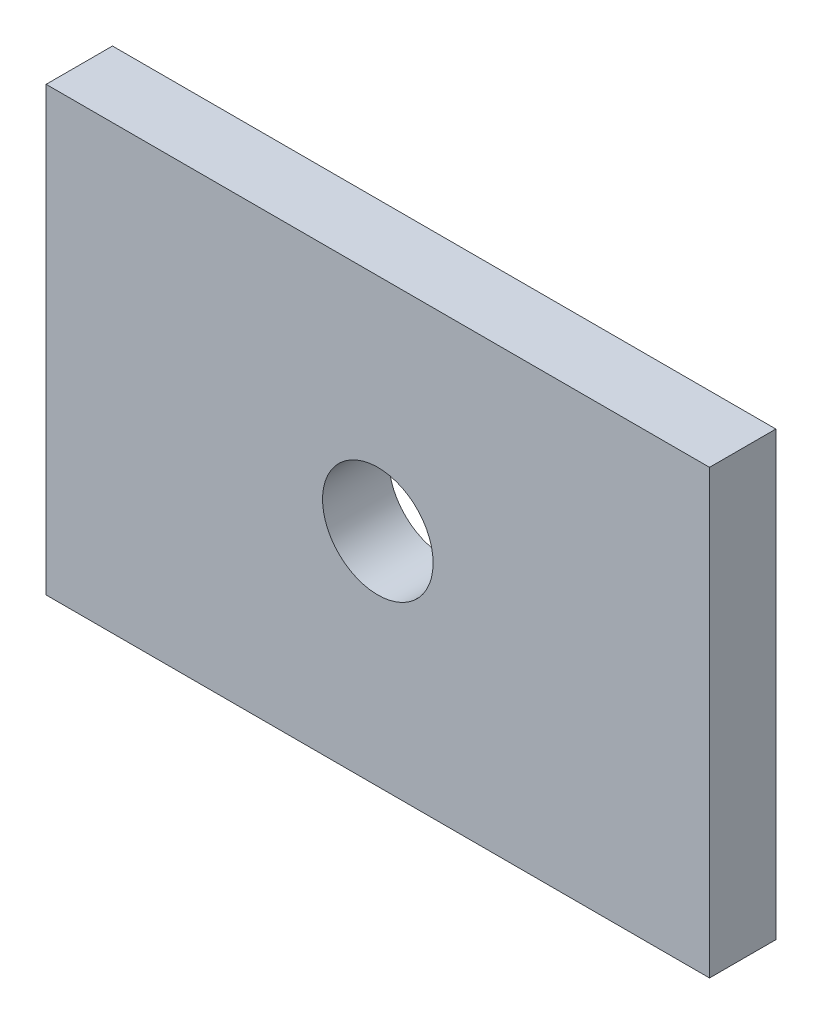
SolidWorks part; units mm, degrees
material "PETG"
ref_plane "Front Plane" through (0, 0, 0) normal (0, 0, 1) x (1, 0, 0)
ref_plane "Top Plane" through (0, 0, 0) normal (0, 1, 0) x (1, 0, 0)
ref_plane "Right Plane" through (0, 0, 0) normal (1, 0, 0) x (0, 0, -1)
sketch "Sketch1" plane through (0, 0, 0) normal (0, 0, 1) x (1, 0, 0)
  line L1 (-26.2656, 68.2374) -> (3.7344, 68.2374)
  line L2 (-26.2656, 68.2374) -> (-26.2656, 48.2374)
  line L3 (-26.2656, 48.2374) -> (3.7344, 48.2374)
  line L4 (3.7344, 68.2374) -> (3.7344, 48.2374)
  line L5 (-26.2656, 68.2374) -> (3.7344, 48.2374) construction
  line L6 (-26.2656, 48.2374) -> (3.7344, 68.2374) construction
  point P0 (-11.2656, 58.2374)
extrude "Boss-Extrude2" add sketch "Sketch1" along normal blind 3 contours L1 L4 L3 L2
sketch "Sketch6" plane through (0, 0, 3) normal (0, 0, 1) x (1, 0, 0)
  circle A0 centre (-11.2656, 58.2374) radius 2.5
extrude "Cut-Extrude1" cut sketch "Sketch6" against normal blind 3 contours A0
